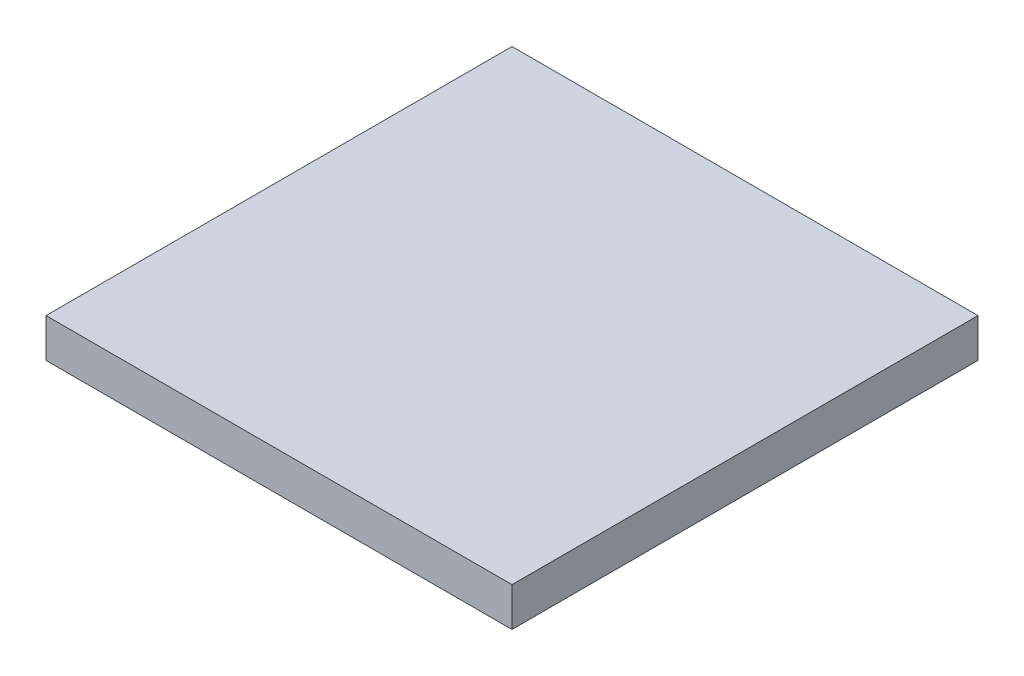
SolidWorks part; units mm, degrees
material "Pino"
ref_plane "Alzado" through (0, 0, 0) normal (0, 0, 1) x (1, 0, 0)
ref_plane "Planta" through (0, 0, 0) normal (0, 1, 0) x (1, 0, 0)
ref_plane "Vista lateral" through (0, 0, 0) normal (1, 0, 0) x (0, 0, -1)
sketch "Croquis1" plane through (0, 0, 0) normal (0, 1, 0) x (1, 0, 0)
  line L1 (-61.4437, 45.7546) -> (118.5563, 45.7546)
  line L2 (-61.4437, 45.7546) -> (-61.4437, -134.2454)
  line L3 (-61.4437, -134.2454) -> (118.5563, -134.2454)
  line L4 (118.5563, 45.7546) -> (118.5563, -134.2454)
  dimension "D1" = 180
  dimension "D2" = 180
extrude "Saliente-Extruir1" add sketch "Croquis1" along normal blind 15
sketch "Croquis2" plane through (0, 15, 0) normal (0, 1, 0) x (1, 0, 0)
  line L8 (-46.4437, 30.7546) -> (-46.4437, -119.2454)
  line L9 (-46.4437, -119.2454) -> (103.5563, -119.2454)
  line L10 (103.5563, -119.2454) -> (103.5563, 30.7546)
  line L11 (103.5563, 30.7546) -> (-46.4437, 30.7546)
  line L12 (-46.4437, 30.7546) -> (-46.4437, -119.2454) construction
  line L13 (-46.4437, -119.2454) -> (103.5563, -119.2454) construction
  line L14 (103.5563, -119.2454) -> (103.5563, 30.7546) construction
  line L15 (103.5563, 30.7546) -> (-46.4437, 30.7546) construction
  dimension "D1" = 15
sketch "Croquis3" plane through (0, 15, 0) normal (0, 1, 0) x (1, 0, 0)
  line L0 (-46.4437, 30.7546) -> (-61.4437, 45.7546) construction
  circle A0 centre (-53.9437, 38.2546) radius 3
  circle A1 centre (111.0563, 38.2546) radius 3
  circle A2 centre (111.0563, -126.7454) radius 3
  circle A3 centre (-53.9437, -126.7454) radius 3
  dimension "D1" = 6
  dimension "D2" = 2
  dimension "D3" = 2
